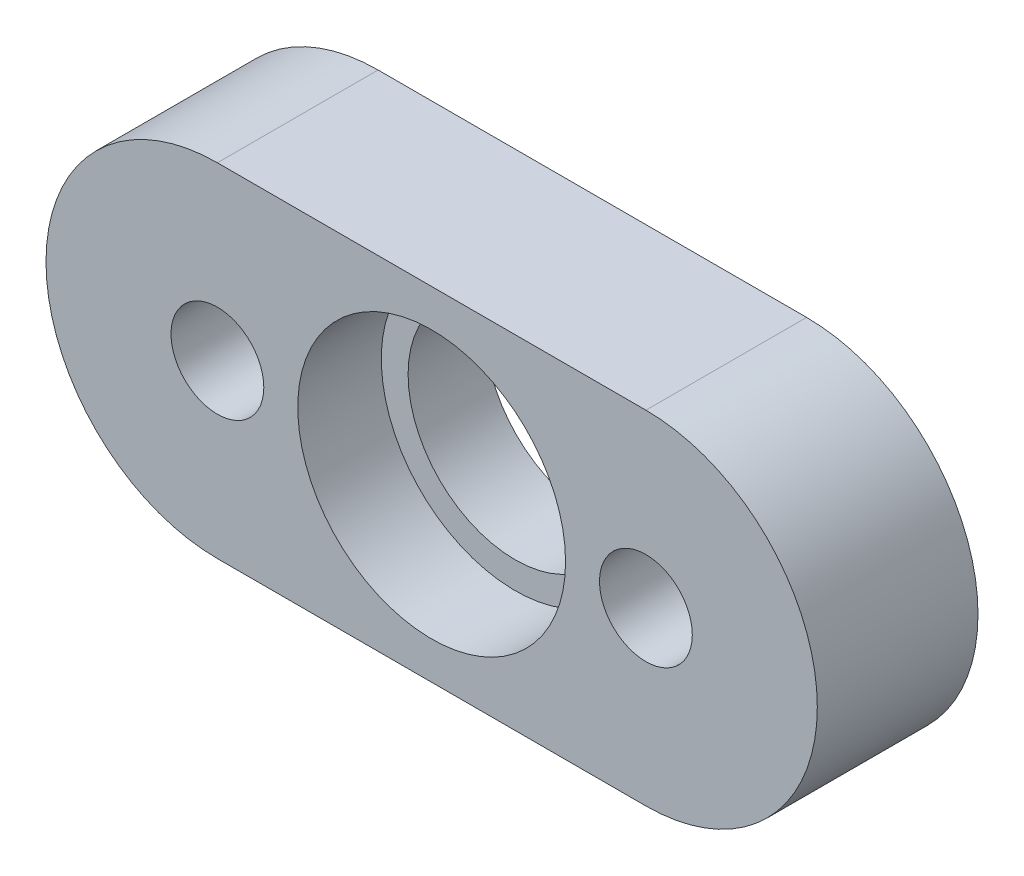
SolidWorks part; units mm, degrees
ref_plane "Front Plane" through (0, 0, 0) normal (0, 0, 1) x (1, 0, 0)
ref_plane "Top Plane" through (0, 0, 0) normal (0, 1, 0) x (1, 0, 0)
ref_plane "Right Plane" through (0, 0, 0) normal (1, 0, 0) x (0, 0, -1)
sketch "Sketch2" plane through (0, 0, 0) normal (0, 0, 1) x (1, 0, 0)
  line L0 (-12.7, 0) -> (12.7, 0) construction
  line L1 (-12.7, 10.16) -> (12.7, 10.16)
  line L2 (-12.7, -10.16) -> (12.7, -10.16)
  arc A0 (-12.7, 10.16) -> (-12.7, -10.16) centre (-12.7, 0) ccw
  arc A1 (12.7, -10.16) -> (12.7, 10.16) centre (12.7, 0) ccw
  point P2 (0, 0)
  dimension "D2" = 10.16
  dimension "D1" = 25.4
extrude "Boss-Extrude5" add sketch "Sketch2" along normal blind 9.525
sketch "Sketch5" plane through (0, 0, 9.525) normal (0, 0, 1) x (1, 0, 0)
  circle A0 centre (0, 0) radius 7.9375
  dimension "D1" = 15.875
extrude "Cut-Extrude3" cut sketch "Sketch5" against normal blind 4.953
sketch "Sketch6" plane through (0, 0, 9.525) normal (0, 0, 1) x (1, 0, 0)
  line L0 (-22.86, 0) -> (22.86, 0) construction
  line L1 (0, 10.16) -> (0, -10.16) construction
  line L2 (12.7, 10.16) -> (-12.7, 10.16) construction
  line L3 (-12.7, -10.16) -> (12.7, -10.16) construction
  circle A0 centre (0, 0) radius 6.35
  arc A1 (-12.7, 10.16) -> (-12.7, -10.16) centre (-12.7, 0) ccw construction
  arc A2 (12.7, -10.16) -> (12.7, 10.16) centre (12.7, 0) ccw construction
  circle A3 centre (-12.7, 0) radius 2.75
  circle A4 centre (12.7, 0) radius 2.75
  dimension "D1" = 12.7
  dimension "D2" = 5.5
  dimension "D3" = 25.4
extrude "Cut-Extrude4" cut sketch "Sketch6" against normal through all
